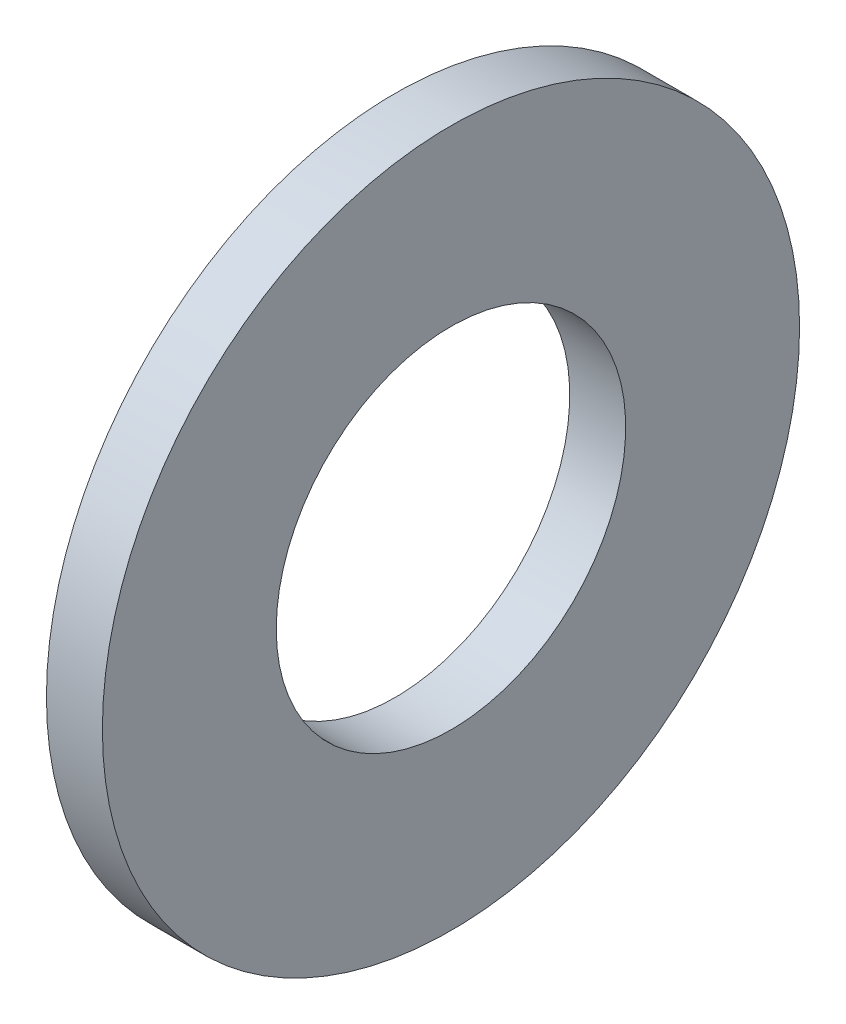
SolidWorks part; units mm, degrees
ref_plane "Front Plane" through (0, 0, 0) normal (0, 0, 1) x (1, 0, 0)
ref_plane "Top Plane" through (0, 0, 0) normal (0, 1, 0) x (1, 0, 0)
ref_plane "Right Plane" through (0, 0, 0) normal (1, 0, 0) x (0, 0, -1)
sketch "Sketch2" plane through (0, 0, 0) normal (0, 0, 1) x (1, 0, 0)
  line L0 (0, 0) -> (9.9406, 0) construction
  line L1 (0, 5.1562) -> (1.651, 5.1562)
  line L2 (0, 5.1562) -> (0, 10.287)
  line L3 (0, 10.287) -> (1.651, 10.287)
  line L4 (1.651, 5.1562) -> (1.651, 10.287)
  point P7 (0, 0)
  dimension "D1" = 20.574
  dimension "D2" = 10.3124
  dimension "D3" = 1.651
revolve "Revolve1" add sketch "Sketch2" angle 360 about L0
